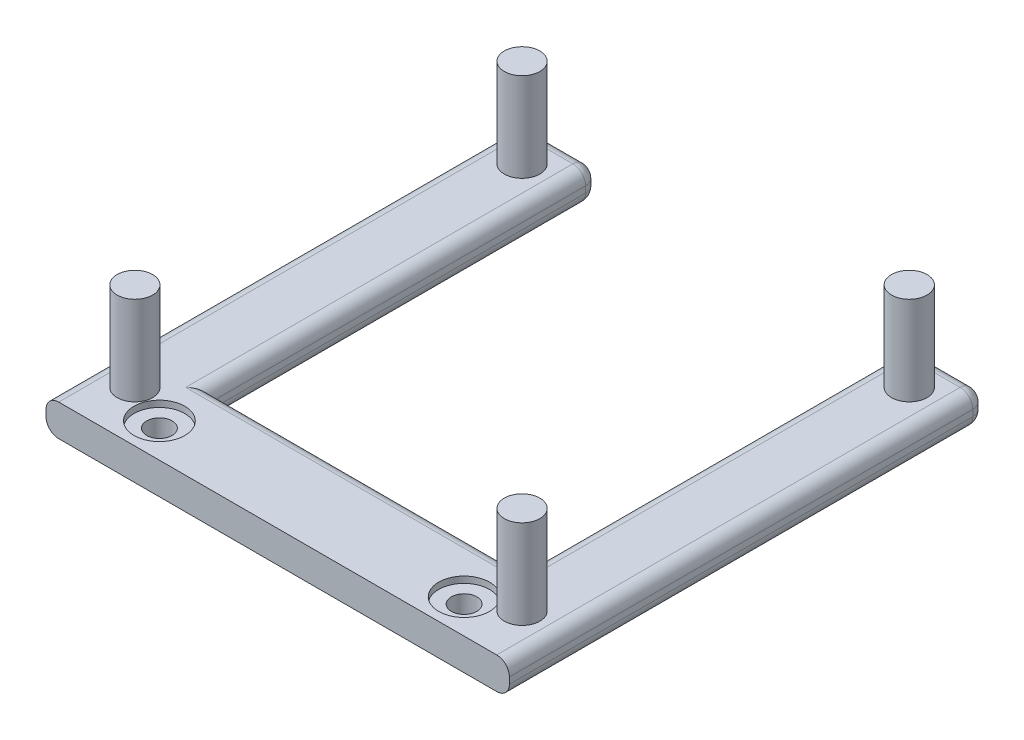
SolidWorks part; units mm, degrees
ref_plane "Front Plane" through (0, 0, 0) normal (0, 0, 1) x (1, 0, 0)
ref_plane "Top Plane" through (0, 0, 0) normal (0, 1, 0) x (1, 0, 0)
ref_plane "Right Plane" through (0, 0, 0) normal (1, 0, 0) x (0, 0, -1)
sketch "Sketch1" plane through (0, 0, 0) normal (0, 1, 0) x (1, 0, 0)
  line L1 (15.25, 15.25) -> (-15.25, 15.25) construction
  line L2 (15.25, 15.25) -> (15.25, -15.25) construction
  line L3 (15.25, -15.25) -> (-15.25, -15.25) construction
  line L4 (-15.25, 15.25) -> (-15.25, -15.25) construction
  line L5 (15.25, 15.25) -> (-15.25, -15.25) construction
  line L6 (15.25, -15.25) -> (-15.25, 15.25) construction
  circle A0 centre (-15.25, -15.25) radius 1.4
  circle A1 centre (-15.25, 15.25) radius 1.4
  circle A2 centre (15.25, 15.25) radius 1.4
  circle A3 centre (15.25, -15.25) radius 1.4
  point P8 (0, 0)
  point P9 (0, 0)
  point P10 (0, 0)
  point P12 (0, 0)
  point P14 (0, 0)
  dimension "D3" = 2.8
  dimension "D1" = 30.5
  dimension "D2" = 30.5
extrude "Boss-Extrude1" add sketch "Sketch1" along normal blind 7
sketch "Sketch2" plane through (0, 0, 0) normal (0, -1, 0) x (1, 0, 0)
  line L3 (-12.25, 12.25) -> (12.25, 12.25)
  line L6 (-18.25, 19.25) -> (-18.25, -18.25)
  line L7 (-18.25, -18.25) -> (-12.25, -18.25)
  line L8 (-12.25, 12.25) -> (-12.25, -18.25)
  line L9 (18.25, 19.25) -> (-18.25, 19.25)
  line L10 (18.25, 19.25) -> (18.25, -18.25)
  line L11 (18.25, -18.25) -> (12.25, -18.25)
  line L12 (12.25, 12.25) -> (12.25, -18.25)
  circle A0 centre (-15.25, -15.25) radius 1.4 construction
  circle A1 centre (15.25, -15.25) radius 1.4 construction
  circle A2 centre (-15.25, 15.25) radius 1.4 construction
  point P2 (0, 0)
  point P9 (0, 0)
  point P12 (0, 0)
  point P13 (0, 0)
  dimension "D1" = 3
  dimension "D2" = 3
  dimension "D4" = 3
  dimension "D5" = 3
  dimension "D8" = 4
  dimension "D3" = 6
  dimension "D6" = 6
  dimension "D7" = 3
extrude "Boss-Extrude2" add sketch "Sketch2" along normal blind 2.5
fillet "Fillet1" radius 1 18 edges at (18.25, 0, 0.5) (15.25, 0, -18.25) (12.25, 0, -3) (-18.25, 0, 0.5) (-15.25, 0, -18.25) (0, 0, 12.25) (-12.25, 0, -3) (-18.25, -2.5, 0.5) (-15.25, -2.5, -18.25) (-12.25, -2.5, -3) (0, -2.5, 12.25) (12.25, -2.5, -3) (15.25, -2.5, -18.25) (18.25, -2.5, 0.5) (18.25, -1.25, -18.25) (12.25, -1.25, -18.25) (-12.25, -1.25, -18.25) (-18.25, -1.25, -18.25)
sketch "Sketch3" plane through (0, -2.5, 0) normal (0, -1, 0) x (1, 0, 0)
  line L0 (17.25, 19.25) -> (-17.25, 19.25) construction
  line L1 (-15.25, 19.25) -> (-9.25, 19.25)
  line L2 (-15.25, 19.25) -> (-15.25, 13.25)
  line L3 (-15.25, 13.25) -> (-9.25, 13.25)
  line L4 (-9.25, 19.25) -> (-9.25, 13.25)
  line L5 (-13.25, 13.25) -> (13.25, 13.25) construction
  line L7 (9.25, 19.25) -> (15.25, 19.25)
  line L8 (9.25, 19.25) -> (9.25, 13.25)
  line L9 (9.25, 13.25) -> (15.25, 13.25)
  line L10 (15.25, 19.25) -> (15.25, 13.25)
  circle A1 centre (-15.25, 15.25) radius 1.4 construction
  circle A2 centre (-15.25, 15.25) radius 1.4 construction
  circle A3 centre (15.25, 15.25) radius 1.4 construction
  circle A4 centre (15.25, 15.25) radius 1.4 construction
extrude "Boss-Extrude3" [suppressed] add sketch "Sketch3" along normal blind 10
sketch "Sketch4" plane through (0, 0, 0) normal (0, 1, 0) x (1, 0, 0)
  line L0 (-18.25, -19.25) -> (-18.25, 17.25) construction
  circle A0 centre (-12, -16.5663) radius 1
  circle A1 centre (12, -16.5663) radius 1
  point P4 (0, 0)
  dimension "D1" = 2
  dimension "D2" = 24
  dimension "D3" = 6.25
extrude "Cut-Extrude1" cut sketch "Sketch4" against normal through all both and the other way through all
sketch "Sketch5" plane through (0, 0, 0) normal (0, 1, 0) x (1, 0, 0)
  circle A0 centre (-12, -16.5663) radius 2
  circle A1 centre (12, -16.5663) radius 2
  dimension "D1" = 4
extrude "Cut-Extrude2" cut sketch "Sketch5" against normal blind 0.5
